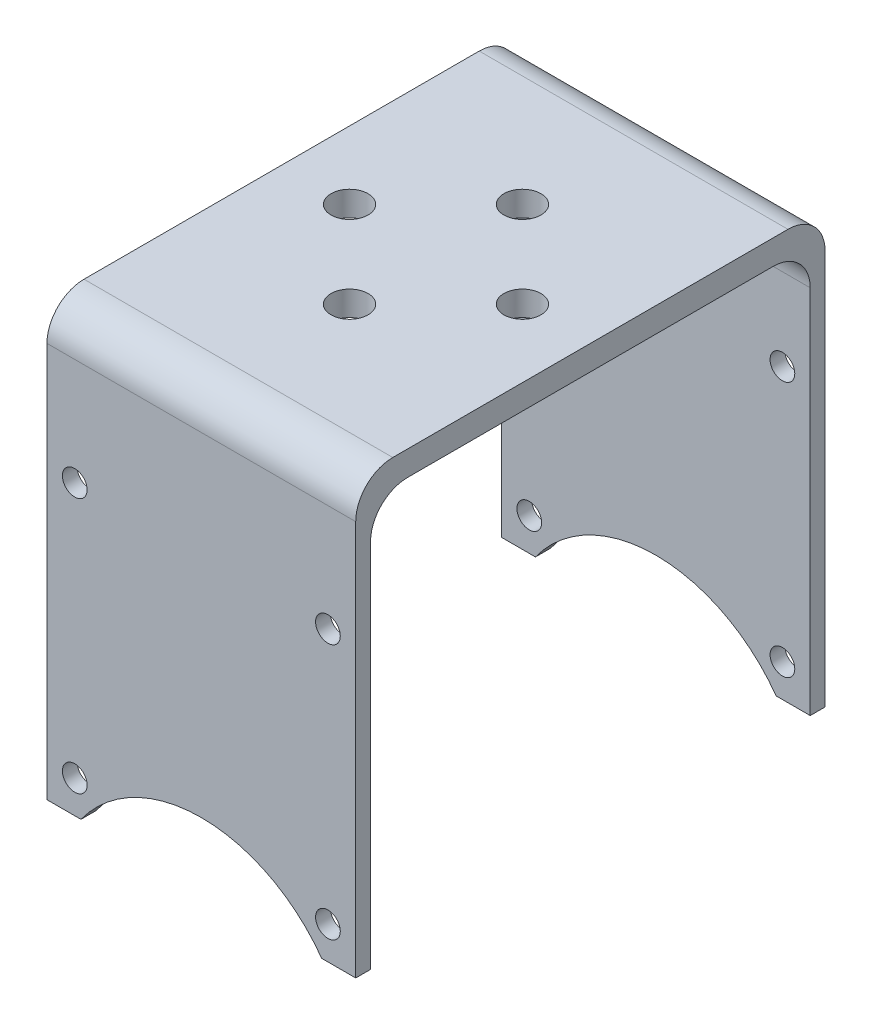
SolidWorks part; units mm, degrees
ref_plane "前视基准面" through (0, 0, 0) normal (0, 0, 1) x (1, 0, 0)
ref_plane "上视基准面" through (0, 0, 0) normal (0, 1, 0) x (1, 0, 0)
ref_plane "右视基准面" through (0, 0, 0) normal (1, 0, 0) x (0, 0, -1)
sketch "草图1" plane through (0, 0, 0) normal (0, 1, 0) x (1, 0, 0)
  line L0 (12.5, -10) -> (12.5, -19)
  line L1 (-20.5, 10) -> (-12.5, 10)
  line L2 (-20.5, 10) -> (-20.5, -10)
  line L3 (-20.5, -10) -> (-12.5, -10)
  line L4 (20.5, 10) -> (20.5, -10)
  line L5 (-20.5, 10) -> (20.5, -10) construction
  line L6 (-20.5, -10) -> (20.5, 10) construction
  line L7 (-12.5, 19) -> (12.5, 19)
  line L8 (-12.5, 19) -> (-12.5, 10)
  line L9 (-12.5, -19) -> (12.5, -19)
  line L10 (12.5, 19) -> (12.5, 10)
  line L11 (-12.5, 19) -> (12.5, -19) construction
  line L12 (-12.5, -19) -> (12.5, 19) construction
  line L13 (12.5, -10) -> (20.5, -10)
  line L14 (-12.5, -10) -> (-12.5, -19)
  line L15 (12.5, 10) -> (20.5, 10)
  point P0 (0, 0)
  point P6 (0, 0)
  dimension "D1" = 41
  dimension "D2" = 20
  dimension "D3" = 25
  dimension "D4" = 38
extrude "凸台-拉伸1" add sketch "草图1" along normal blind 2
sketch "草图2" plane through (0, 2, 0) normal (0, 1, 0) x (1, 0, 0)
  line L0 (-20.5, -10) -> (-12.5, -10) construction
  line L1 (-20.5, 10) -> (-18.5, 10)
  line L2 (-20.5, 10) -> (-20.5, -10)
  line L3 (-20.5, -10) -> (-18.5, -10)
  line L4 (-18.5, 10) -> (-18.5, -10)
  line L5 (12.5, -10) -> (20.5, -10) construction
  line L6 (20.5, 10) -> (18.5, 10)
  line L7 (20.5, 10) -> (20.5, -10)
  line L8 (20.5, -10) -> (18.5, -10)
  line L9 (18.5, 10) -> (18.5, -10)
  dimension "D1" = 2
  dimension "D2" = 2
sketch "草图4" plane through (0, 0, 0) normal (0, -1, 0) x (1, 0, 0)
  line L0 (12.5, 19) -> (12.5, 10) construction
  line L1 (-12.5, 19) -> (12.5, 19)
  line L2 (-12.5, 19) -> (-12.5, 17.8)
  line L3 (-12.5, 17.8) -> (12.5, 17.8)
  line L4 (12.5, 19) -> (12.5, 17.8)
  line L5 (-12.5, -19) -> (-12.5, -10) construction
  line L6 (12.5, -19) -> (-12.5, -19)
  line L7 (12.5, -19) -> (12.5, -17.8)
  line L8 (12.5, -17.8) -> (-12.5, -17.8)
  line L9 (-12.5, -19) -> (-12.5, -17.8)
  dimension "D1" = 1.2
  dimension "D2" = 1.2
extrude "凸台-拉伸3" add sketch "草图4" along normal blind 40
fillet "圆角2" radius 3 4 edges at (0, 0, -17.8) (0, 2, -19) (0, 2, 19) (0, 0, 17.8)
sketch "草图5" plane through (0, 0, -19) normal (0, 0, -1) x (-1, 0, 0)
  line L0 (0, -46.7705) -> (0, 23.5536) construction
  line L1 (-25.8926, 0) -> (22.9009, 0) construction
  line L2 (12.5, -1) -> (12.5, -40) construction
  line L3 (-12.5, -1) -> (-12.5, -40) construction
  line L4 (-12.5, -20) -> (-12.5, -40)
  line L5 (-12.5, -40) -> (12.5, -40)
  line L6 (12.5, -40) -> (12.5, -20)
  arc A0 (12.5, -20) -> (-12.5, -20) centre (0, -20) cw
  circle A1 centre (0, -20) radius 4.5
  circle A2 centre (0, -20) radius 7 construction
  circle A3 centre (0, -13) radius 1.5
  circle A4 centre (7, -20) radius 1.5
  circle A5 centre (0, -27) radius 1.5
  circle A6 centre (-7, -20) radius 1.5
  point P29 (0, -20)
  dimension "D2" = 9
  dimension "D3" = 14
  dimension "D4" = 3
  dimension "D1" = 20
  dimension "D5" = 4
sketch "草图7" plane through (0, 0, 19) normal (0, 0, 1) x (1, 0, 0)
  line L0 (0, -46.3202) -> (0, 14.2704) construction
  line L1 (-25.5668, 0) -> (26.1896, 0) construction
  line L2 (-12.5, -33) -> (-9.7468, -33)
  line L3 (-10.25, -30.35) -> (10.25, -30.35) construction
  line L4 (-10.25, -30.35) -> (-10.25, -9.65) construction
  line L5 (-10.25, -9.65) -> (10.25, -9.65) construction
  line L6 (10.25, -30.35) -> (10.25, -9.65) construction
  line L7 (-10.25, -30.35) -> (10.25, -9.65) construction
  line L8 (-10.25, -9.65) -> (10.25, -30.35) construction
  line L9 (-12.5, -1) -> (-12.5, -40) construction
  line L10 (12.5, -1) -> (12.5, -40) construction
  line L11 (12.5, -33) -> (12.5, -40)
  line L12 (12.5, -40) -> (-12.5, -40)
  line L13 (-12.5, -40) -> (-12.5, -33)
  line L14 (9.7468, -33) -> (12.5, -33)
  circle A0 centre (-10.25, -30.35) radius 1
  circle A1 centre (-10.25, -9.65) radius 1
  circle A2 centre (10.25, -9.65) radius 1
  circle A3 centre (10.25, -30.35) radius 1
  arc A4 (-9.7468, -33) -> (9.7468, -33) centre (0, -40) cw
  point P5 (0, -20)
  dimension "D4" = 2
  dimension "D5" = 2
  dimension "D6" = 2
  dimension "D7" = 2
  dimension "D10" = 12
  dimension "D1" = 20.5
  dimension "D2" = 20.7
  dimension "D3" = 20
  dimension "D8" = 33
  dimension "D9" = 40
extrude "切除-拉伸3" cut sketch "草图7" against normal through all
sketch "草图8" plane through (0, 2, 0) normal (0, 1, 0) x (1, 0, 0)
  line L1 (-12.5, -19) -> (12.5, -19)
  line L2 (-12.5, -19) -> (-12.5, 19)
  line L3 (-12.5, 19) -> (12.5, 19)
  line L4 (12.5, -19) -> (12.5, 19)
  line L5 (-12.5, -19) -> (12.5, 19) construction
  line L6 (-12.5, 19) -> (12.5, -19) construction
  point P0 (0, 0)
extrude "切除-拉伸4" cut sketch "草图8" against normal blind 10 flip side to cut
sketch "草图9" plane through (0, 2, 0) normal (0, 1, 0) x (1, 0, 0)
  line L0 (0, -23.5037) -> (0, 23.9778) construction
  line L1 (-15.5046, 0) -> (14.3195, 0) construction
  circle A0 centre (0, 0) radius 7 construction
  circle A1 centre (0, 7) radius 1.5
  circle A2 centre (7, 0) radius 1.5
  circle A3 centre (0, -7) radius 1.5
  circle A4 centre (-7, 0) radius 1.5
  point P18 (0, 0)
  dimension "D1" = 14
  dimension "D2" = 3
  dimension "D3" = 4
extrude "切除-拉伸5" cut sketch "草图9" against normal blind 10
